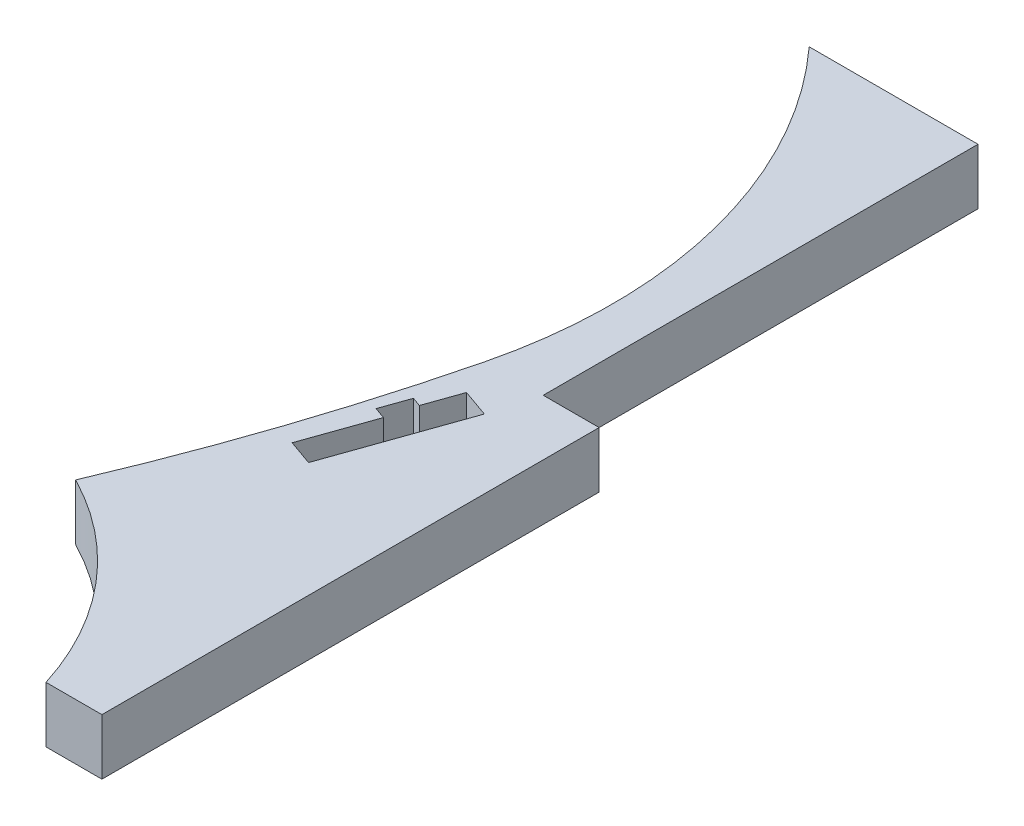
SolidWorks part; units mm, degrees
material "Pine"
ref_plane "Front Plane" through (0, 0, 0) normal (0, 0, 1) x (1, 0, 0)
ref_plane "Top Plane" through (0, 0, 0) normal (0, 1, 0) x (1, 0, 0)
ref_plane "Right Plane" through (0, 0, 0) normal (1, 0, 0) x (0, 0, -1)
sketch "Sketch1" plane through (0, 0, 0) normal (0, 1, 0) x (1, 0, 0)
  line L62 (-86.9348, 33.6872) -> (-73.7224, 64.7656) construction
  line L68 (0, 169.3886) -> (0, 0)
  line L74 (-19.05, 0) -> (0, 0)
  line L84 (-19.05, 317.5) -> (-19.05, 0) construction
  line L85 (0, 317.5) -> (-19.05, 317.5) construction
  line L86 (0, 169.3886) -> (-19.05, 169.3886)
  line L87 (-19.05, 169.3886) -> (-19.05, 317.5)
  line L89 (0, 317.5) -> (0, 169.3886) construction
  line L90 (-19.05, 317.5) -> (-76.5548, 317.5)
  arc A12 (-73.7224, 64.7656) -> (-38.8765, 169.3886) centre (-704.9171, 333.1067) ccw
  arc A13 (-73.7224, 64.7656) -> (-19.05, 0) centre (-123.825, -32.9878) cw
  arc A15 (-38.8765, 169.3886) -> (-76.5548, 317.5) centre (-196.51, 208.1362) ccw
  dimension "D5" = 162.3259
  dimension "D2" = 33.7703
  dimension "D8" = 57.5048
  dimension "D9" = 109.8453
  dimension "D4" = 19.05
  dimension "D7" = 23.032
  dimension "D6" = 685.8671
  dimension "D3" = 169.3886
  dimension "D1" = 317.5
extrude "Boss-Extrude1" add sketch "Sketch1" along normal blind 19.05
sketch "Sketch2" plane through (0, 19.05, 0) normal (0, 1, 0) x (1, 0, 0)
  line L0 (-39.808, 110.8665) -> (-45.7961, 112.9797) construction
  line L1 (-39.0895, 110.6129) -> (-39.808, 110.8665) construction
  line L2 (-33.1811, 129.6451) -> (-39.1692, 131.7583) construction
  line L3 (-32.4626, 129.3915) -> (-33.1811, 129.6451) construction
  line L4 (-39.0895, 110.6129) -> (-32.4626, 129.3915) construction
  line L5 (-19.05, 317.5) -> (-76.5548, 317.5)
  line L6 (-19.05, 169.3886) -> (-19.05, 317.5)
  line L7 (0, 169.3886) -> (-19.05, 169.3886)
  line L8 (0, 0) -> (0, 169.3886)
  line L18 (-19.05, 0) -> (0, 0)
  line L19 (-19.05, 317.5) -> (-76.5548, 317.5)
  line L20 (-19.05, 169.3886) -> (-19.05, 317.5)
  line L21 (0, 169.3886) -> (-19.05, 169.3886)
  line L22 (0, 0) -> (0, 169.3886)
  line L23 (-19.05, 0) -> (0, 0)
  line L24 (-39.808, 110.8665) -> (-45.7961, 112.9797) construction
  line L25 (-39.0895, 110.6129) -> (-39.808, 110.8665) construction
  line L26 (-33.1811, 129.6451) -> (-39.1692, 131.7583) construction
  line L27 (-32.4626, 129.3915) -> (-33.1811, 129.6451) construction
  line L28 (-39.0895, 110.6129) -> (-32.4626, 129.3915) construction
  line L29 (-45.7961, 112.9797) -> (-46.5147, 113.2332) construction
  line L30 (-45.7961, 112.9797) -> (-46.5147, 113.2332) construction
  line L31 (-39.5835, 132.8741) -> (-46.5147, 113.2332) construction
  line L32 (-39.5835, 132.8741) -> (-46.5147, 113.2332) construction
  line L33 (-38.8649, 132.6205) -> (-39.5835, 132.8741) construction
  line L34 (-38.8649, 132.6205) -> (-39.5835, 132.8741) construction
  line L35 (-39.1692, 131.7583) -> (-38.8649, 132.6205) construction
  line L37 (-40.6636, 137.0262) -> (-33.1665, 134.3805) construction
  line L38 (-31.1412, 135.3493) -> (-25.3681, 151.7087) construction
  line L39 (-30.8278, 155.3189) -> (-26.3368, 153.734) construction
  line L40 (-36.5132, 143.9788) -> (-32.8532, 154.3501) construction
  line L41 (-40.6636, 137.0262) -> (-33.1665, 134.3805) construction
  line L42 (-31.1412, 135.3493) -> (-25.3681, 151.7087) construction
  line L43 (-30.8278, 155.3189) -> (-26.3368, 153.734) construction
  line L44 (-36.5132, 143.9788) -> (-32.8532, 154.3501) construction
  line L46 (-40.6636, 137.0262) -> (-42.2924, 137.601) construction
  line L47 (-42.2924, 137.601) -> (-39.6509, 145.0861) construction
  line L48 (-39.6509, 145.0861) -> (-36.5132, 143.9788) construction
  line L49 (-42.2924, 137.601) -> (-39.6509, 145.0861) construction
  line L50 (-39.1641, 109.5618) -> (-23.5436, 153.8257)
  line L51 (-23.5436, 153.8257) -> (-32.9448, 157.1434)
  line L52 (-32.9448, 157.1434) -> (-37.1331, 145.275)
  line L53 (-37.1331, 145.275) -> (-40.2709, 146.3823)
  line L54 (-40.2709, 146.3823) -> (-43.5886, 136.981)
  line L55 (-43.5886, 136.981) -> (-39.6963, 135.6075)
  line L56 (-39.6963, 135.6075) -> (-47.8109, 112.6133)
  line L57 (-47.8109, 112.6133) -> (-39.1641, 109.5618)
  line L58 (-28.5823, 154.5264) -> (-28.2442, 155.4845) construction
  line L59 (-28.2546, 143.529) -> (-27.2966, 143.1909) construction
  line L60 (-34.6832, 149.1645) -> (-35.6412, 149.5026) construction
  line L61 (-40.9716, 141.3435) -> (-41.9297, 141.6817) construction
  line L62 (-39.6509, 145.0861) -> (-39.3128, 146.0442) construction
  line L63 (-40.6636, 137.0262) -> (-41.0017, 136.0681) construction
  line L64 (-43.0491, 123.0537) -> (-44.0072, 123.3918) construction
  line L65 (-42.8021, 111.9231) -> (-43.1402, 110.965) construction
  arc A3 (-33.1665, 134.3805) -> (-31.1412, 135.3493) centre (-32.6383, 135.8776) ccw construction
  arc A4 (-25.3681, 151.7087) -> (-26.3368, 153.734) centre (-26.8651, 152.237) ccw construction
  arc A8 (-30.8278, 155.3189) -> (-32.8532, 154.3501) centre (-31.3561, 153.8218) ccw construction
  arc A9 (-19.05, 0) -> (-73.7224, 64.7656) centre (-123.825, -32.9878) ccw
  arc A10 (-73.7224, 64.7656) -> (-38.8765, 169.3886) centre (-704.9171, 333.1067) ccw
  arc A11 (-38.8765, 169.3886) -> (-76.5548, 317.5) centre (-196.51, 208.1362) ccw
  arc A12 (-19.05, 0) -> (-73.7224, 64.7656) centre (-123.825, -32.9878) ccw
  arc A13 (-73.7224, 64.7656) -> (-38.8765, 169.3886) centre (-704.9171, 333.1067) ccw
  arc A14 (-38.8765, 169.3886) -> (-76.5548, 317.5) centre (-196.51, 208.1362) ccw
  circle A15 centre (-30.2733, 150.9751) radius 1.8415 construction
  circle A16 centre (-34.4996, 138.999) radius 1.8415 construction
  arc A17 (-33.1665, 134.3805) -> (-31.1412, 135.3493) centre (-32.6383, 135.8776) ccw construction
  arc A18 (-25.3681, 151.7087) -> (-26.3368, 153.734) centre (-26.8651, 152.237) ccw construction
  arc A19 (-30.8278, 155.3189) -> (-32.8532, 154.3501) centre (-31.3561, 153.8218) ccw construction
  circle A20 centre (-30.2733, 150.9751) radius 1.8415 construction
  circle A21 centre (-34.4996, 138.999) radius 1.8415 construction
  point P41 (-28.2442, 155.4845)
  dimension "D2" = 1.016
  dimension "D1" = 0
extrude "Cut-Extrude2" cut sketch "Sketch2" against normal through all contours L54 L55 L56 L57 L50 L51 L52 L53
hole_wizard "1/8 (0.125) Diameter Hole1" positions "Sketch3" profile "Sketch4" hole size "1/8" standard "ANSI Inch"
sketch "Sketch3" plane through (0, 0, 0) normal (0, -1, 0) x (-1, 0, 0)
  line L0 (9.525, 0) -> (9.525, 169.3886) construction
  line L1 (19.05, 0) -> (0, 0) construction
  line L2 (0, 169.3886) -> (19.05, 169.3886) construction
  line L5 (12.7, 28.575) -> (38.3632, 73.025) construction
  line L8 (38.3632, 73.025) -> (38.3632, 300.0375) construction
  line L11 (12.7, 28.575) -> (9.525, 28.575) construction
  line L13 (38.3632, 73.025) -> (9.525, 73.025) construction
  line L15 (38.3632, 300.0375) -> (38.3632, 317.5) construction
  line L16 (19.05, 317.5) -> (76.5548, 317.5) construction
  point P0 (12.7, 28.575)
  point P2 (38.3632, 73.025)
  point P4 (38.3632, 300.0375)
  dimension "D1" = 28.575
  dimension "D2" = 3.175
  dimension "D3" = 44.45
  dimension "D4" = 30
  dimension "D5" = 17.4625
sketch "Sketch4" plane through (-12.7, 0, -28.575) normal (1, 0, 0) x (0, 0, -1)
  line L0 (0, 0) -> (0, 12.0791)
  line L1 (0, 12.0791) -> (1.5875, 11.1252)
  line L2 (1.5875, 11.1252) -> (1.5875, 0)
  line L5 (1.5875, 0) -> (0, 0)
  line L10 (0, 12.0791) -> (-1.5875, 11.1252) construction
  line L11 (0, -6.35) -> (0, 107.95) construction
  dimension "Hole Dia." = 3.175
  dimension "Hole Depth" = 11.1252
  dimension "Drill Angle" = 118
